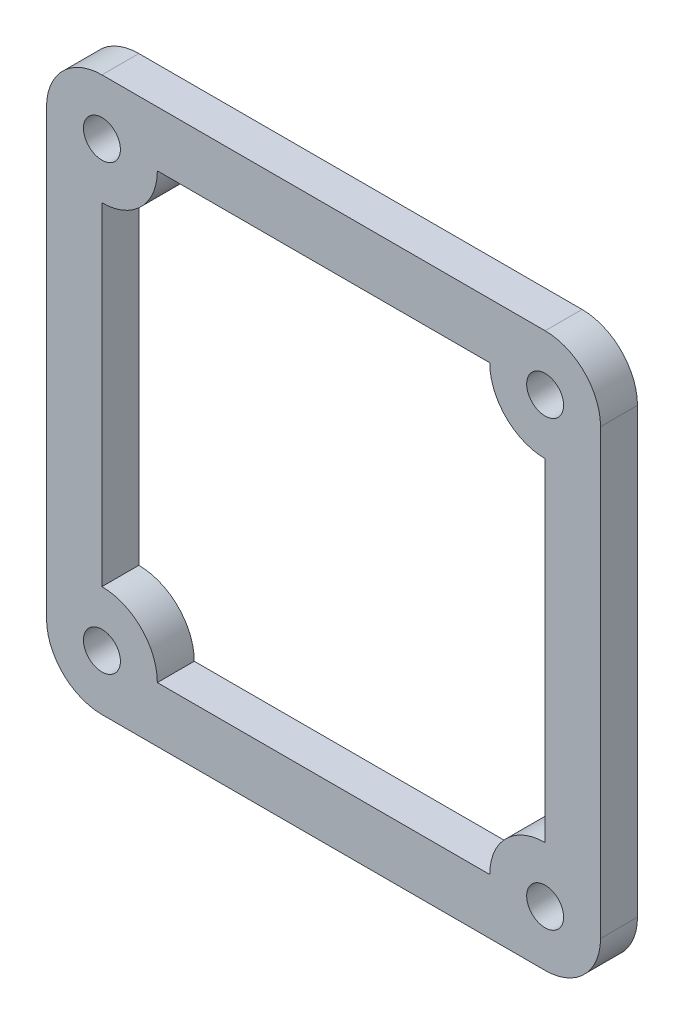
SolidWorks part; units mm, degrees
ref_plane "Alzado" through (0, 0, 0) normal (0, 0, 1) x (1, 0, 0)
ref_plane "Planta" through (0, 0, 0) normal (0, 1, 0) x (1, 0, 0)
ref_plane "Vista lateral" through (0, 0, 0) normal (1, 0, 0) x (0, 0, -1)
sketch "Model" plane through (0, 0, 0) normal (0, 0, 1) x (1, 0, 0)
  line L0 (-105.9434, 101.0565) -> (-105.9434, 65.0565)
  line L1 (-101.4434, 60.5565) -> (-65.4434, 60.5565)
  line L2 (-60.9434, 65.0565) -> (-60.9434, 101.0565)
  line L3 (-65.4434, 105.5565) -> (-101.4434, 105.5565)
  line L4 (-101.4434, 96.5565) -> (-101.4434, 69.5565)
  line L5 (-96.9434, 65.0565) -> (-69.9434, 65.0565)
  line L6 (-65.4434, 69.5565) -> (-65.4434, 96.5565)
  line L7 (-69.9434, 101.0565) -> (-96.9434, 101.0565)
  circle A0 centre (-101.4434, 101.0565) radius 1.5
  circle A1 centre (-65.4434, 101.0565) radius 1.5
  arc A2 (-101.4434, 105.5565) -> (-105.9434, 101.0565) centre (-101.4434, 101.0565) ccw
  arc A3 (-60.9434, 101.0565) -> (-65.4434, 105.5565) centre (-65.4434, 101.0565) ccw
  arc A4 (-105.9434, 65.0565) -> (-101.4434, 60.5565) centre (-101.4434, 65.0565) ccw
  arc A5 (-65.4434, 60.5565) -> (-60.9434, 65.0565) centre (-65.4434, 65.0565) ccw
  circle A6 centre (-101.4434, 65.0565) radius 1.5
  circle A7 centre (-65.4434, 65.0565) radius 1.5
  arc A8 (-101.4434, 96.5565) -> (-96.9434, 101.0565) centre (-101.4434, 101.0565) ccw
  arc A9 (-69.9434, 101.0565) -> (-65.4434, 96.5565) centre (-65.4434, 101.0565) ccw
  arc A10 (-65.4434, 69.5565) -> (-69.9434, 65.0565) centre (-65.4434, 65.0565) ccw
  arc A11 (-96.9434, 65.0565) -> (-101.4434, 69.5565) centre (-101.4434, 65.0565) ccw
extrude "Saliente-Extruir1" add sketch "Model" along normal blind 3
